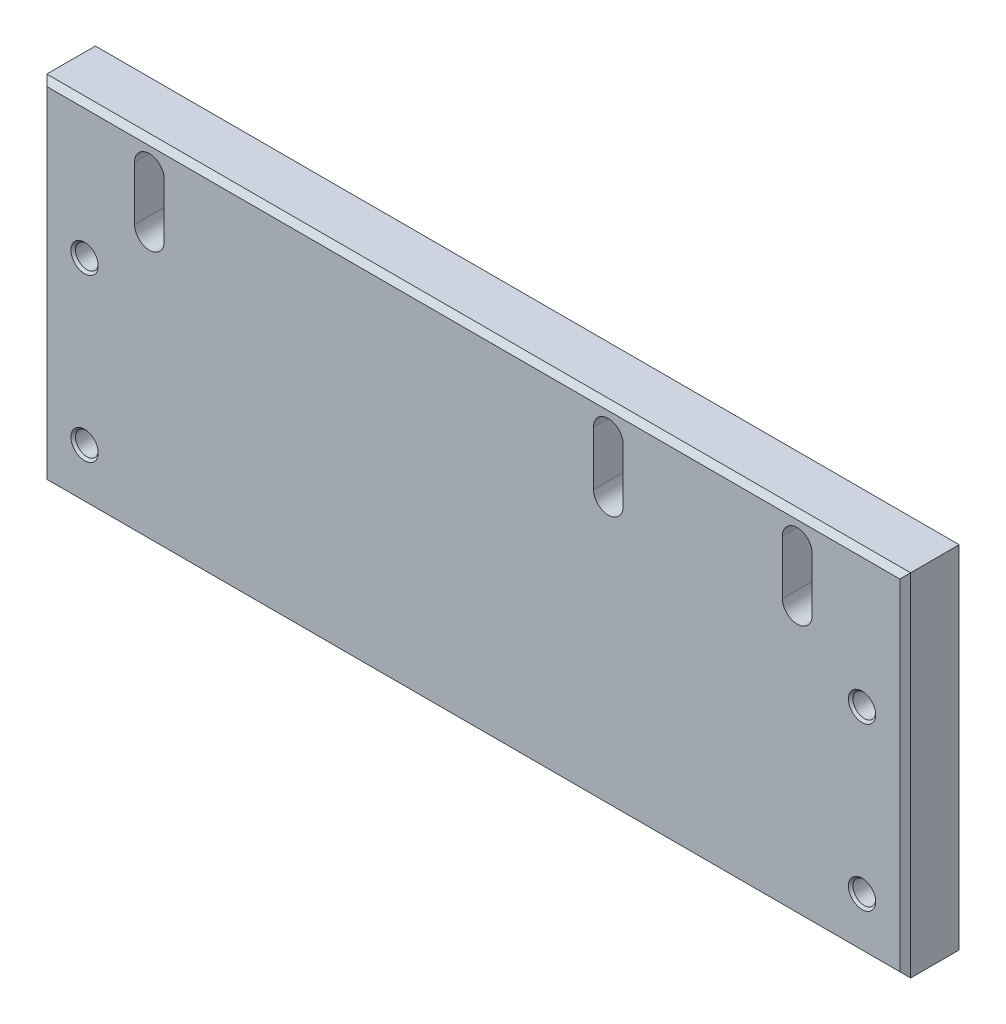
SolidWorks part; units mm, degrees
material "1.4301 (X5CrNi18-10)"
ref_plane "Vorne" through (0, 0, 0) normal (0, 0, 1) x (1, 0, 0)
ref_plane "Oben" through (0, 0, 0) normal (0, 1, 0) x (1, 0, 0)
ref_plane "Rechts" through (0, 0, 0) normal (1, 0, 0) x (0, 0, -1)
sketch "Skizze1" plane through (0, 0, 0) normal (0, 0, 1) x (1, 0, 0)
  line L0 (-80, 32.5) -> (80, -32.5) construction
  line L1 (80, 32.5) -> (-80, 32.5)
  line L2 (-80, 32.5) -> (-80, -32.5)
  line L5 (0, 0) -> (37.4444, 0) construction
  line L9 (0, 0) -> (0, 32.5) construction
  line L10 (-80, -32.5) -> (80, -32.5)
  line L13 (80, -32.5) -> (80, 32.5)
  dimension "D1" = 160
  dimension "D2" = 65
extrude "Aufsatz-Linear austragen1" add sketch "Skizze1" along normal blind 10
hole_wizard "M5 Gewindebohrung1" positions "Skizze3" profile "Skizze2" tap size "M5" standard "DIN"
sketch "Skizze3" plane through (0, 0, 10) normal (0, 0, 1) x (1, 0, 0)
  line L4 (0, 0) -> (0, -19.9088) construction
  line L6 (80, 32.5) -> (-80, 32.5) construction
  point P0 (-72, 7.5)
  point P1 (-72, -22.5)
  point P3 (72, -22.5)
  point P5 (72, 7.5)
  dimension "D1" = 25
  dimension "D3" = 30
  dimension "D4" = 144
sketch "Skizze2" plane through (-72, 7.5, 10) normal (1, 0, 0) x (0, -1, 0)
  line L0 (0, 0) -> (0, 15.2618)
  line L1 (0, 15.2618) -> (2.1, 14)
  line L2 (2.1, 14) -> (2.1, 0.425)
  line L3 (2.1, 0.425) -> (2.525, 0)
  line L5 (2.525, 0) -> (0, 0)
  line L6 (-2.1, 0.425) -> (-2.525, 0) construction
  line L10 (0, 15.2618) -> (-2.1, 14) construction
  line L11 (0, -6.35) -> (0, 107.95) construction
  dimension "Bohrerdurchmesser" = 4.2
  dimension "Bohrungstiefe" = 14
  dimension "Senkdurchmesser (Oben)" = 5.05
  dimension "Senkwinkel (Oben)" = 90
  dimension "Spitzenwinkel" = 118
cosmetic thread "Bohrungsgewinde1" parameters "D1"=10, "D2"=5
cosmetic thread "Bohrungsgewinde2" parameters "D1"=10, "D2"=5
cosmetic thread "Bohrungsgewinde3" parameters "D1"=10, "D2"=5
cosmetic thread "Bohrungsgewinde4" parameters "D1"=10, "D2"=5
sketch "Skizze4" plane through (0, 0, 10) normal (0, 0, 1) x (1, 0, 0)
  line L0 (80, 32.5) -> (-80, 32.5) construction
  line L1 (25, 27.5) -> (25, 17.5) construction
  line L2 (27.75, 27.5) -> (27.75, 17.5)
  line L3 (-42.2008, 0) -> (0, 0) construction
  line L4 (0, 0) -> (0, -25.4218) construction
  line L5 (22.25, 27.5) -> (22.25, 17.5)
  line L8 (60, 17.5) -> (60, 27.5) construction
  line L9 (57.25, 17.5) -> (57.25, 27.5)
  line L10 (62.75, 17.5) -> (62.75, 27.5)
  line L11 (-60, 17.5) -> (-60, 27.5) construction
  line L12 (-57.25, 17.5) -> (-57.25, 27.5)
  line L13 (-62.75, 17.5) -> (-62.75, 27.5)
  arc A0 (27.75, 27.5) -> (22.25, 27.5) centre (25, 27.5) ccw
  arc A1 (22.25, 17.5) -> (27.75, 17.5) centre (25, 17.5) ccw
  arc A4 (57.25, 17.5) -> (62.75, 17.5) centre (60, 17.5) ccw
  arc A5 (62.75, 27.5) -> (57.25, 27.5) centre (60, 27.5) ccw
  arc A6 (-57.25, 17.5) -> (-62.75, 17.5) centre (-60, 17.5) cw
  arc A7 (-62.75, 27.5) -> (-57.25, 27.5) centre (-60, 27.5) cw
  point P4 (25, 22.5)
  point P20 (60, 22.5)
  point P27 (-60, 22.5)
  dimension "D2" = 10
  dimension "D3" = 5
  dimension "D1" = 5.5
  dimension "D4" = 120
  dimension "D5" = 85
extrude "Schnitt-Linear austragen1" cut sketch "Skizze4" against normal through all
chamfer "Fase1" distance 1 angle 45 4 edges at (80, 0, 10) (0, 32.5, 10) (-80, 0, 10) (0, -32.5, 10)
